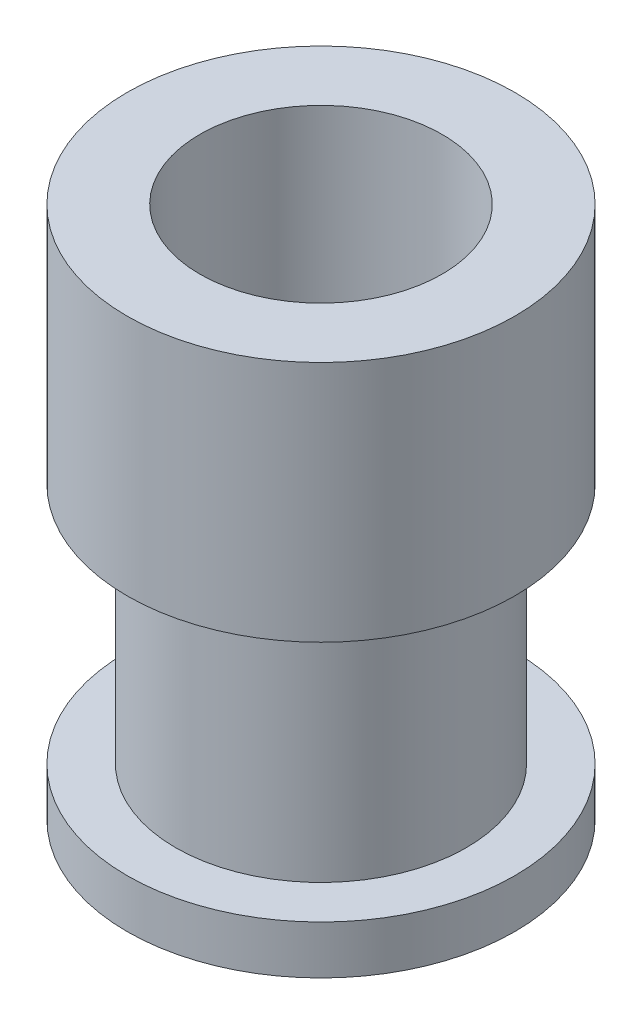
SolidWorks part; units mm, degrees
ref_plane "Front Plane" through (0, 0, 0) normal (0, 0, 1) x (1, 0, 0)
ref_plane "Top Plane" through (0, 0, 0) normal (0, 1, 0) x (1, 0, 0)
ref_plane "Right Plane" through (0, 0, 0) normal (1, 0, 0) x (0, 0, -1)
sketch "Sketch1" plane through (0, 0, 0) normal (0, 1, 0) x (1, 0, 0)
  circle A0 centre (0, 0) radius 25
  circle A1 centre (0, 0) radius 40
  dimension "D1" = 50
  dimension "D2" = 80
extrude "Boss-Extrude1" add sketch "Sketch1" along normal blind 10
sketch "Sketch2" plane through (0, 10, 0) normal (0, 1, 0) x (1, 0, 0)
  circle A0 centre (0, 0) radius 25
  circle A1 centre (0, 0) radius 30
  dimension "D1" = 60
extrude "Boss-Extrude2" add sketch "Sketch2" along normal blind 50
sketch "Sketch3" plane through (0, 60, 0) normal (0, 1, 0) x (1, 0, 0)
  circle A0 centre (0, 0) radius 25
  circle A1 centre (0, 0) radius 40
extrude "Boss-Extrude3" add sketch "Sketch3" along normal blind 50
sketch "Sketch4" plane through (0, 110, 0) normal (0, 1, 0) x (1, 0, 0)
  circle A0 centre (0, 0) radius 25 construction
  circle A1 centre (0, 0) radius 25
curve "Helix/Spiral1" pitch 10 height 108 turns 10.8
